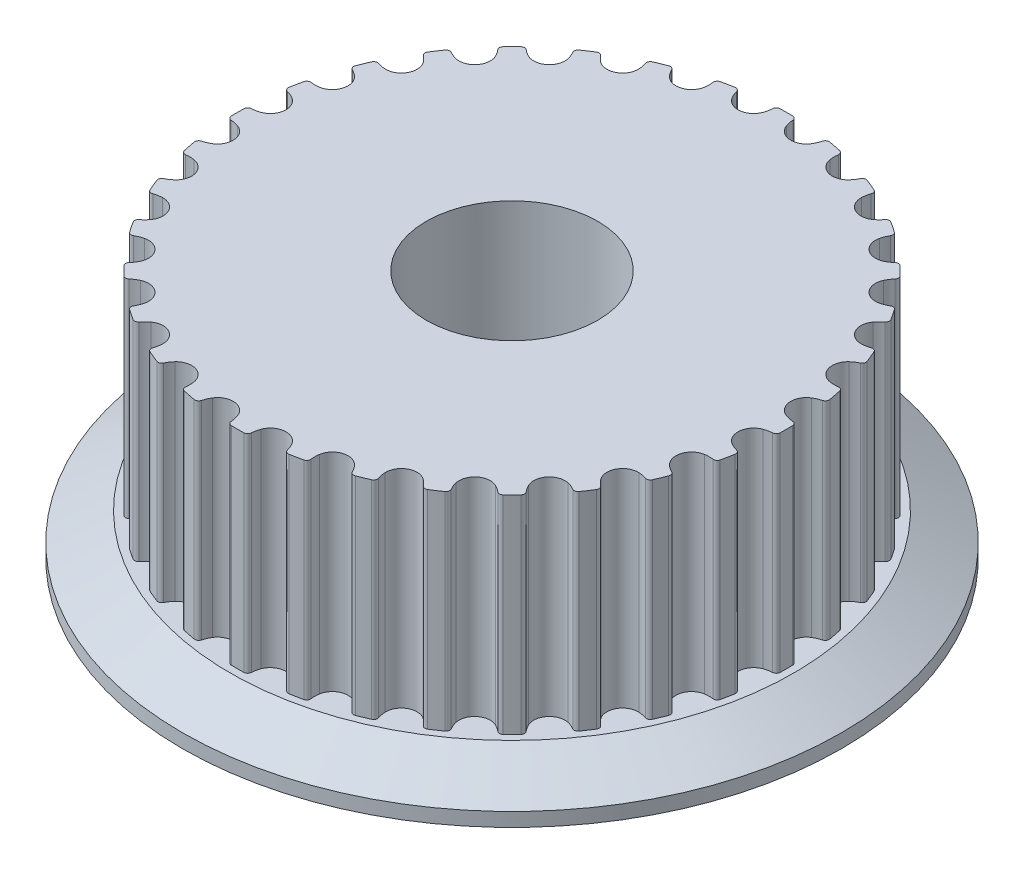
SolidWorks part; units mm, degrees
ref_plane "Front" through (0, 0, 0) normal (0, 0, 1) x (1, 0, 0)
ref_plane "Top" through (0, 0, 0) normal (0, 1, 0) x (1, 0, 0)
ref_plane "Right" through (0, 0, 0) normal (1, 0, 0) x (0, 0, -1)
sketch "Sketch1" plane through (0, 0, 0) normal (0, 1, 0) x (1, 0, 0)
  line L0 (0, 0) -> (0, 10.1859) construction
  line L1 (0, 9.9319) -> (0, 10.5619)
  line L2 (0, 0) -> (0.9984, 10.1369) construction
  line L3 (1.9376, 9.7411) -> (2.0605, 10.359)
  line L4 (1.3715, 9.8451) -> (1.4054, 10.0885) construction
  arc A0 (0.2268, 9.9293) -> (0.3731, 9.7879) centre (0.2234, 9.7794) cw
  arc A1 (0.3731, 9.7879) -> (0.4342, 9.4966) centre (1.3715, 9.8451) ccw
  circle A2 centre (0, 0) radius 10.1859 construction
  arc A3 (0.2268, 9.9293) -> (0, 9.9319) centre (0, 0) ccw
  arc A4 (0.9, 9.1377) -> (0, 9.1819) centre (0, 0) ccw construction
  arc A5 (0.4342, 9.4966) -> (1.4269, 9.3988) centre (0.9544, 9.69) ccw
  arc A6 (1.3715, 9.8451) -> (0.9743, 9.8923) centre (0, 0) ccw construction
  arc A7 (0, 10.5619) -> (2.0605, 10.359) centre (0, 0) cw
  arc A8 (1.5436, 9.6727) -> (1.4269, 9.3988) centre (0.5756, 9.9235) cw
  arc A9 (1.7147, 9.7828) -> (1.5436, 9.6727) centre (1.6888, 9.635) ccw
  arc A10 (1.7147, 9.7828) -> (1.9376, 9.7411) centre (0, 0) cw
  dimension "D1" = 0.15
  dimension "D4" = 20.3718
  dimension "D5" = 1
  dimension "D7" = 0.555
  dimension "D3" = 5.625
  dimension "D8" = 0.75
  dimension "D6" = 0.254
  dimension "D2" = 0.4
  dimension "D9" = 1.38
  dimension "D11" = 0.4099
  dimension "D12" = 0.2457
  dimension "D10" = 2.306
sketch "Sketch2" plane through (0, 0, 0) normal (0, 1, 0) x (1, 0, 0)
  circle A0 centre (0, 0) radius 10.1859 construction
  circle A1 centre (0, 0) radius 10.1859
  circle A2 centre (0, 0) radius 3.1
  dimension "D1" = 6.2
extrude "Boss-Extrude1" add sketch "Sketch2" along normal mid plane 10
sketch "Sketch6" plane through (0, 0, 0) normal (0, 1, 0) x (1, 0, 0)
  line L0 (0, 9.9219) -> (0, 10.5619)
  line L1 (1.9357, 9.7313) -> (2.0605, 10.359)
  arc A7 (2.0605, 10.359) -> (0, 10.5619) centre (0, 0) ccw construction
  arc A8 (2.0605, 10.359) -> (0, 10.5619) centre (0, 0) ccw
  arc A14 (1.713, 9.7729) -> (1.5533, 9.6702) centre (1.6888, 9.635) ccw
  arc A15 (1.4354, 9.3936) -> (1.5533, 9.6702) centre (0.5756, 9.9235) ccw
  arc A16 (0.4248, 9.4931) -> (1.4354, 9.3936) centre (0.9544, 9.69) ccw
  arc A17 (0.3631, 9.7874) -> (0.4248, 9.4931) centre (1.3715, 9.8451) ccw
  arc A18 (0.3631, 9.7874) -> (0.2266, 9.9193) centre (0.2234, 9.7794) ccw
  arc A19 (0.2266, 9.9193) -> (0, 9.9219) centre (0, 0) ccw
  arc A20 (1.9357, 9.7313) -> (1.713, 9.7729) centre (0, 0) ccw
  arc A21 (1.713, 9.7729) -> (1.5533, 9.6702) centre (1.6888, 9.635) ccw
  arc A22 (1.4354, 9.3936) -> (1.5533, 9.6702) centre (0.5756, 9.9235) ccw
  arc A23 (0.4248, 9.4931) -> (1.4354, 9.3936) centre (0.9544, 9.69) ccw
  arc A24 (0.3631, 9.7874) -> (0.4248, 9.4931) centre (1.3715, 9.8451) ccw
  arc A25 (0.3631, 9.7874) -> (0.2266, 9.9193) centre (0.2234, 9.7794) ccw
  arc A26 (0.2266, 9.9193) -> (0, 9.9219) centre (0, 0) ccw
  arc A27 (1.9357, 9.7313) -> (1.713, 9.7729) centre (0, 0) ccw
extrude "Cut-Extrude3" cut sketch "Sketch6" against normal through all both and the other way through all
pattern_circular "CirPattern3" count 32 over 360 about axis through (0, 0, 0) along (0, 1, 0) of "Cut-Extrude3"
sketch "Sketch3" plane through (0, 0, 0) normal (0, 0, 1) x (1, 0, 0)
  line L0 (0, 0) -> (0, 9.5108) construction
  line L1 (-10.1859, 5) -> (-11.918, 6)
  line L2 (-11.918, 6) -> (-11.918, 6.5)
  line L3 (-11.918, 6.5) -> (-3.1, 6.5)
  line L4 (-3.1, 6.5) -> (-3.1, 5)
  line L5 (-3.1, 5) -> (-10.1859, 5)
  line L6 (3.1, 5) -> (-3.1, 5) construction
  dimension "D4" = 20.3718
  dimension "D1" = 1.5
  dimension "D2" = 0.5
  dimension "D3" = 30
revolve "Revolve1" add sketch "Sketch3" angle 360 about L0
mirror "Mirror1" about plane through (0, 0, 0) normal (0, 1, 0) of "Revolve1"
sketch "Sketch4" plane through (0, 0, 0) normal (0, 0, 1) x (1, 0, 0)
  line L0 (0, 0) -> (0, 14.0175) construction
  line L1 (11.918, 6.5) -> (-11.918, 6.5) construction
  line L2 (-3.1, 6.5) -> (-9.6, 6.5)
  line L3 (-3.1, 6.5) -> (-3.1, 12.5)
  line L4 (-3.1, 12.5) -> (-9.6, 12.5)
  line L5 (-9.6, 6.5) -> (-9.6, 12.5)
  dimension "D2" = 6
  dimension "D1" = 6.5
revolve "Revolve2" add sketch "Sketch4" angle 360 about L0
sketch "Sketch5" plane through (0, 0, 0) normal (0, 0, 1) x (1, 0, 0)
  line L1 (0, 6.5) -> (0, 12.5) construction
  line L2 (9.6, 12.5) -> (-9.6, 12.5) construction
  line L7 (-9.6, 12.5) -> (-9.6, 6.5) construction
  line L8 (-9.6, 12.5) -> (-9.6, 6.5) construction
  circle A0 centre (0, 9.5) radius 1.6
  dimension "D1" = 3.2
extrude "Cut-Extrude2" cut sketch "Sketch5" along normal through all
pattern_circular "CirPattern2" count 2 over 90 about axis through (0, 5, 0) along (0, -1, 0) of "Cut-Extrude2"
sketch "Sketch7" plane through (0, 12.5, 0) normal (0, 1, 0) x (1, 0, 0)
  circle A0 centre (0, 0) radius 18
extrude "Cut-Extrude4" cut sketch "Sketch7" against normal blind 10
equation "\"belt-step\" = 2"
equation "\"pulley-teeth\" = 32"
equation "\"pulley-dia\"= ( \"belt-step\" * \"pulley-teeth\" ) / Pi"
equation "\"D3@Sketch1\"=(360/\"pulley-teeth\")/2"
equation "\"D4@Sketch1\"=\"pulley-dia\""
equation "\"bore-dia\" = 6.2"
equation "\"belt-thick\"= 10"
equation "\"D4@Sketch3\"=\"pulley-dia\""
equation "\"D1@Sketch2\"=\"bore-dia\""
equation "\"D1@Boss-Extrude1\"=\"belt-thick\""
equation "\"teeth-offset\"= 0.01"
equation "\"D1@Sketch6\"=\"teeth-offset\""
equation "\"D1@CirPattern3\"=\"pulley-teeth\""
equation "\"flange-wall\"= 6.5"
equation "\"D1@Sketch4\"=\"flange-wall\""
equation "\"flange-h\"= 6"
equation "\"screw-dia\"= 3.2"
equation "\"D2@Sketch4\"=\"flange-h\""
equation "\"D1@Sketch5\"=\"screw-dia\""
equation "\"D10@Sketch1\"=(0.4/(Pi*(\"pulley-dia\"-(2*\"D12@Sketch1\"))))*360"
